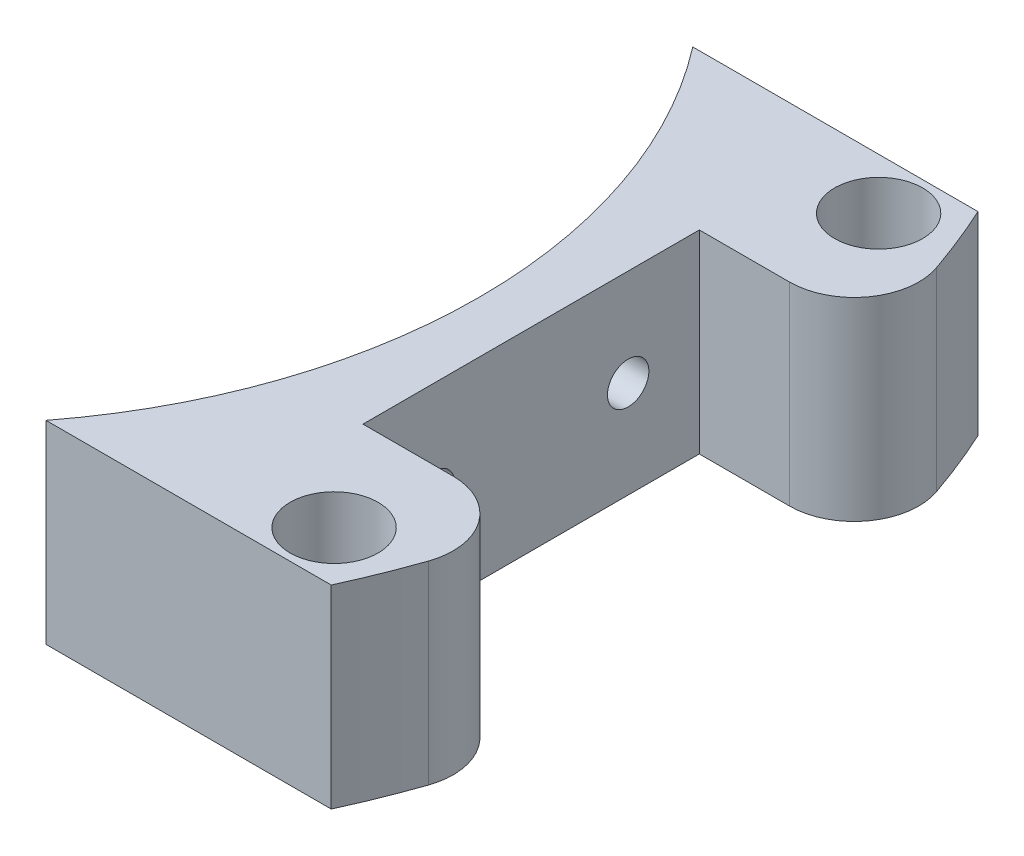
SolidWorks part; units mm, degrees
ref_plane "前视基准面" through (0, 0, 0) normal (0, 0, 1) x (1, 0, 0)
ref_plane "上视基准面" through (0, 0, 0) normal (0, 1, 0) x (1, 0, 0)
ref_plane "右视基准面" through (0, 0, 0) normal (1, 0, 0) x (0, 0, -1)
other "Configuration Table"
sketch "草图1" plane through (0, 0, 0) normal (0, 1, 0) x (1, 0, 0)
  line L3 (98.223, -107.4405) -> (93.8568, -95.4444)
  line L4 (-40.4497, 75.7097) -> (22.0464, 75.7097)
  line L5 (-7.9536, 50.7097) -> (22.0464, 50.7097)
  line L6 (-7.9536, 50.7097) -> (-7.9536, 100.7097)
  line L7 (-7.9536, 100.7097) -> (22.0464, 100.7097)
  line L8 (22.0464, 50.7097) -> (22.0464, 100.7097)
  circle A3 centre (-40.4497, 75.7097) radius 30
  circle A13 centre (10.3636, 96.7573) radius 3.4
  circle A14 centre (10.3636, 54.6621) radius 3.4
  circle A15 centre (-40.4497, 75.7097) radius 41
  circle A16 centre (-40.4497, 75.7097) radius 60
  dimension "D1" = 60
  dimension "D2" = 6.8
  dimension "D8" = 82
  dimension "D11" = 120
  dimension "D3" = 10.3636
  dimension "D4" = 40.4497
  dimension "D5" = 54.6621
  dimension "D6" = 75.7097
  dimension "D7" = 96.7573
  dimension "D9" = 50
  dimension "D10" = 30
extrude "凸台-拉伸2" add sketch "草图1" along normal blind 15 contours A15 L5 L8 L4 A14 | A15 L4 L8 L7 A13
sketch "草图2" plane through (0, 15, 0) normal (0, 1, 0) x (1, 0, 0)
  line L0 (-40.4497, 75.7097) -> (19.5503, 75.7097)
  line L1 (24.5503, 88.7097) -> (4.5503, 88.7097)
  line L2 (24.5503, 88.7097) -> (24.5503, 62.7097)
  line L3 (24.5503, 62.7097) -> (4.5503, 62.7097)
  line L4 (4.5503, 88.7097) -> (4.5503, 62.7097)
  line L6 (-7.9536, 50.7097) -> (14.0938, 50.7097)
  line L7 (14.0938, 100.7097) -> (-7.9536, 100.7097)
  line L8 (-7.9536, 50.7097) -> (14.0938, 50.7097)
  line L9 (14.0938, 100.7097) -> (-7.9536, 100.7097)
  arc A3 (14.0938, 50.7097) -> (14.0938, 100.7097) centre (-40.4497, 75.7097) ccw
  arc A4 (-7.9536, 50.7097) -> (-7.9536, 100.7097) centre (-40.4497, 75.7097) ccw
  arc A5 (14.0938, 50.7097) -> (14.0938, 100.7097) centre (-40.4497, 75.7097) ccw
  arc A6 (-7.9536, 50.7097) -> (-7.9536, 100.7097) centre (-40.4497, 75.7097) ccw
  point P4 (21.9983, 62.7097)
  arc M12 (14.0938, 50.7097) -> (14.0938, 100.7097) centre (-40.4497, 75.7097) ccw
  dimension "D1" = 0
  dimension "D2" = 45
  dimension "D3" = 13
  dimension "D4" = 13
  dimension "D5" = 20
extrude "切除-拉伸1" cut sketch "草图2" against normal through all contours L1 L4 L0 M12 | L0 L4 L3 M12
sketch "草图4" plane through (4.5503, 0, 0) normal (1, 0, 0) x (0, 0, -1)
  line L0 (62.7097, 7.5) -> (88.7097, 7.5)
  line L1 (62.7097, 0) -> (62.7097, 15) construction
  line L2 (88.7097, 0) -> (88.7097, 15) construction
  line L3 (75.7097, 15) -> (75.7097, 0)
  line L4 (88.7097, 15) -> (62.7097, 15) construction
  line L5 (88.7097, 0) -> (62.7097, 0) construction
  circle A0 centre (68.2097, 7.5) radius 1.6
  circle A1 centre (83.2097, 7.5) radius 1.6
  dimension "D1" = 7.5
  dimension "D2" = 7.5
  dimension "D3" = 3.2
  dimension "D4" = 3.2
extrude "切除-拉伸2" cut sketch "草图4" against normal through all contours L0 A1 | L0 A1 | L0 A0 | L0 A0
ref_plane "基准面1" through (-7.9536, 0, 0) normal (-1, 0, 0) x (0, 0, 1)
sketch "草图6" plane through (-7.9536, 0, 0) normal (-1, 0, 0) x (0, 0, 1)
  circle A0 centre (-83.2097, 7.5) radius 1.6 construction
  circle A1 centre (-83.2097, 7.5) radius 1.6
  circle A2 centre (-68.2097, 7.5) radius 1.6 construction
  circle A3 centre (-68.2097, 7.5) radius 1.6
  circle A4 centre (-83.2097, 7.5) radius 2.5
  circle A5 centre (-68.2097, 7.5) radius 2.5
  dimension "D1" = 5
  dimension "D2" = 5
extrude "切除-拉伸3" cut sketch "草图6" against normal blind 10
fillet "圆角1" radius 5 2 edges at (18.125, 7.5, -88.7097) (18.125, 7.5, -62.7097)
